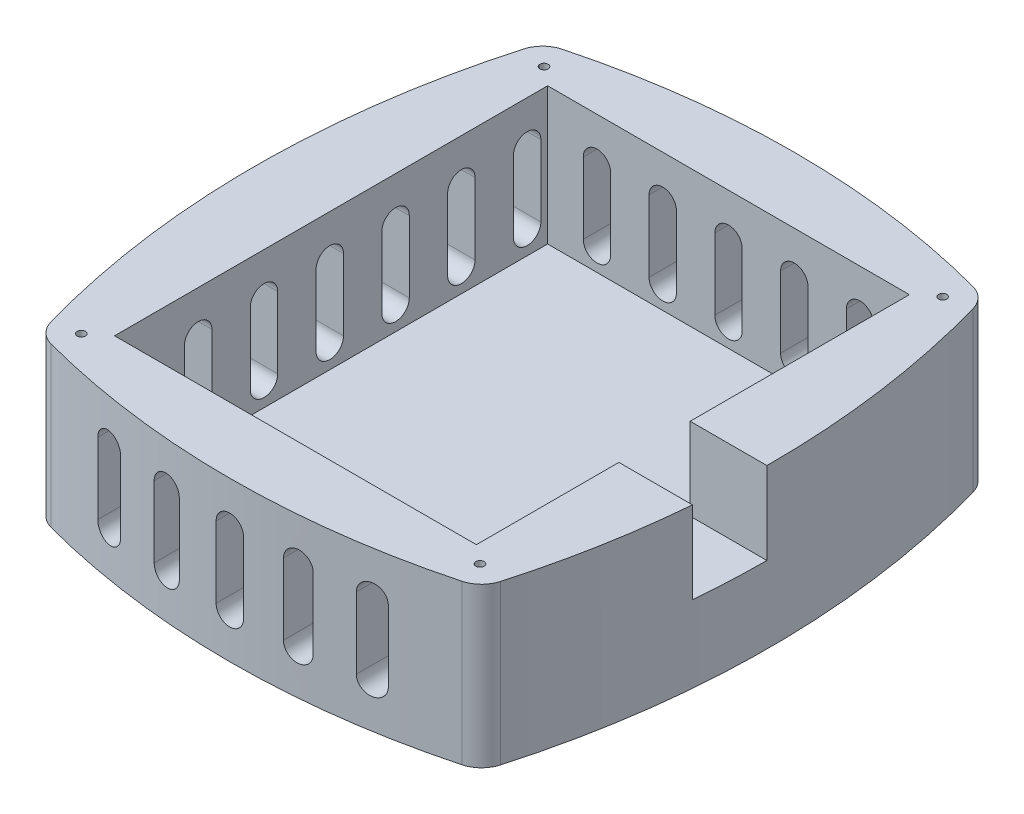
SolidWorks part; units mm, degrees
ref_plane "Front Plane" through (0, 0, 0) normal (0, 0, 1) x (1, 0, 0)
ref_plane "Top Plane" through (0, 0, 0) normal (0, 1, 0) x (1, 0, 0)
ref_plane "Right Plane" through (0, 0, 0) normal (1, 0, 0) x (0, 0, -1)
sketch "Sketch1" plane through (0, 0, 0) normal (0, 1, 0) x (1, 0, 0)
  line L0 (39.2475, 50.0745) -> (39.2475, -28.9255)
  line L1 (39.2475, -28.9255) -> (-26.7525, -28.9255)
  line L2 (-26.7525, -28.9255) -> (-26.7525, 50.0745)
  line L3 (-26.7525, 50.0745) -> (39.2475, 50.0745)
  dimension "D1" = 79
  dimension "D2" = 66
extrude "Boss-Extrude1" add sketch "Sketch1" along normal blind 4
sketch "Sketch2" plane through (0, 0, 0) normal (0, -1, 0) x (1, 0, 0)
  line L0 (-30.7525, 32.9255) -> (-30.7525, -54.0745)
  line L1 (-30.7525, -54.0745) -> (43.2475, -54.0745)
  line L2 (43.2475, -54.0745) -> (43.2475, 32.9255)
  line L3 (43.2475, 32.9255) -> (-30.7525, 32.9255)
  line L4 (-26.7525, -50.0745) -> (39.2475, -50.0745)
  line L5 (39.2475, -50.0745) -> (39.2475, 28.9255)
  line L6 (39.2475, 28.9255) -> (-26.7525, 28.9255)
  line L7 (-26.7525, 28.9255) -> (-26.7525, -50.0745)
  line L8 (-26.7525, -50.0745) -> (39.2475, -50.0745)
  line L9 (39.2475, -50.0745) -> (39.2475, 28.9255)
  line L10 (39.2475, 28.9255) -> (-26.7525, 28.9255)
  line L11 (-26.7525, 28.9255) -> (-26.7525, -50.0745)
  dimension "D1" = 0
  dimension "D2" = 4
extrude "Boss-Extrude2" add sketch "Sketch2" against normal blind 29
sketch "Sketch4" plane through (0, 0, 0) normal (0, -1, 0) x (1, 0, 0)
  line L0 (-30.7525, 32.9255) -> (-30.7525, -54.0745) construction
  line L1 (-30.7525, -10.5745) -> (43.2475, -10.5745) construction
  line L2 (43.2475, -54.0745) -> (43.2475, 32.9255) construction
  line L3 (6.2475, 32.9255) -> (6.2475, -10.5745) construction
  line L4 (43.2475, 32.9255) -> (-30.7525, 32.9255) construction
  line L5 (43.2475, 32.9255) -> (-30.7525, 32.9255) construction
  line L9 (-30.7525, -54.0745) -> (43.2475, -54.0745) construction
  line L10 (-30.7525, 32.9255) -> (-30.7525, -54.0745) construction
  line L11 (43.2475, 32.9255) -> (-30.7525, 32.9255)
  line L12 (43.2475, -54.0745) -> (43.2475, 32.9255)
  line L15 (-30.7525, -54.0745) -> (43.2475, -54.0745)
  line L16 (-30.7525, 32.9255) -> (-30.7525, -54.0745)
  arc A0 (-40.7525, -10.5745) -> (-34.7525, 32.5476) centre (117.2068, -10.5745) cw
  arc A1 (-40.7525, -10.5745) -> (-34.7525, -53.6965) centre (117.2068, -10.5745) ccw
  arc A2 (-34.7525, 32.5476) -> (-31.2309, 36.0137) centre (-29.9424, 31.1826) cw
  arc A3 (-31.2309, 36.0137) -> (6.2475, 40.9255) centre (6.2475, -104.5161) cw
  arc A4 (47.2475, 32.5476) -> (43.7258, 36.0137) centre (42.4374, 31.1826) ccw
  arc A5 (43.7258, 36.0137) -> (6.2475, 40.9255) centre (6.2475, -104.5161) ccw
  arc A6 (53.2475, -10.5745) -> (47.2475, -53.6965) centre (-104.7118, -10.5745) cw
  arc A7 (53.2475, -10.5745) -> (47.2475, 32.5476) centre (-104.7118, -10.5745) ccw
  arc A8 (-34.7525, -53.6965) -> (-31.2309, -57.1627) centre (-29.9424, -52.3316) ccw
  arc A9 (-31.2309, -57.1627) -> (6.2475, -62.0745) centre (6.2475, 83.3671) ccw
  arc A10 (43.7258, -57.1627) -> (6.2475, -62.0745) centre (6.2475, 83.3671) cw
  arc A11 (47.2475, -53.6965) -> (43.7258, -57.1627) centre (42.4374, -52.3316) cw
  dimension "D4" = 8
  dimension "D5" = 5
  dimension "D1" = 10
  dimension "D2" = 86.2441
  dimension "D3" = 4
extrude "Boss-Extrude4" add sketch "Sketch4" against normal up to surface (29 mm away) up to face at (6.2475, 29, -10.5745)
sketch "Sketch3" plane through (0, 29, 0) normal (0, 1, 0) x (1, 0, 0)
  line L0 (39.2475, -28.9255) -> (39.2475, 50.0745) construction
  line L1 (39.2475, 10.0745) -> (55.4463, 10.0745)
  line L2 (39.2475, 10.0745) -> (39.2475, -2.9255)
  line L3 (39.2475, -2.9255) -> (55.4463, -2.9255)
  line L6 (39.2475, 50.0745) -> (-26.7525, 50.0745) construction
  line L7 (-26.7525, 50.0745) -> (39.2475, 50.0745) construction
  line L8 (55.4463, -2.9255) -> (55.4463, 10.0745)
  dimension "D1" = 40
  dimension "D2" = 53
extrude "Cut-Extrude1" cut sketch "Sketch3" against normal blind 15
sketch "Sketch5" plane through (-26.7525, 0, 0) normal (1, 0, 0) x (0, 0, -1)
  line L0 (10.3372, 21.1129) -> (10.3372, 8.1129) construction
  line L1 (12.8372, 21.1129) -> (12.8372, 8.1129)
  line L2 (7.8372, 21.1129) -> (7.8372, 8.1129)
  line L3 (22.3372, 21.1129) -> (22.3372, 8.1129) construction
  line L4 (24.8372, 21.1129) -> (24.8372, 8.1129)
  line L5 (19.8372, 21.1129) -> (19.8372, 8.1129)
  line L6 (34.3372, 21.1129) -> (34.3372, 8.1129) construction
  line L7 (36.8372, 21.1129) -> (36.8372, 8.1129)
  line L8 (31.8372, 21.1129) -> (31.8372, 8.1129)
  line L9 (46.3372, 21.1129) -> (46.3372, 8.1129) construction
  line L10 (48.8372, 21.1129) -> (48.8372, 8.1129)
  line L11 (43.8372, 21.1129) -> (43.8372, 8.1129)
  line L12 (10.3372, 21.1129) -> (10.3372, 8.1129) construction
  line L13 (12.8372, 21.1129) -> (12.8372, 8.1129)
  line L14 (7.8372, 21.1129) -> (7.8372, 8.1129)
  line L15 (22.3372, 21.1129) -> (22.3372, 8.1129) construction
  line L16 (24.8372, 21.1129) -> (24.8372, 8.1129)
  line L17 (19.8372, 21.1129) -> (19.8372, 8.1129)
  line L18 (34.3372, 21.1129) -> (34.3372, 8.1129) construction
  line L19 (36.8372, 21.1129) -> (36.8372, 8.1129)
  line L20 (31.8372, 21.1129) -> (31.8372, 8.1129)
  line L21 (-1.6628, 21.1129) -> (-1.6628, 8.1129) construction
  line L22 (0.8372, 21.1129) -> (0.8372, 8.1129)
  line L23 (-4.1628, 21.1129) -> (-4.1628, 8.1129)
  line L24 (10.3372, 21.1129) -> (10.3372, 8.1129) construction
  line L25 (12.8372, 21.1129) -> (12.8372, 8.1129)
  line L26 (7.8372, 21.1129) -> (7.8372, 8.1129)
  line L27 (22.3372, 21.1129) -> (22.3372, 8.1129) construction
  line L28 (24.8372, 21.1129) -> (24.8372, 8.1129)
  line L29 (19.8372, 21.1129) -> (19.8372, 8.1129)
  line L30 (-13.6628, 21.1129) -> (-13.6628, 8.1129) construction
  line L31 (-11.1628, 21.1129) -> (-11.1628, 8.1129)
  line L32 (-16.1628, 21.1129) -> (-16.1628, 8.1129)
  line L33 (-1.6628, 21.1129) -> (-1.6628, 8.1129) construction
  line L34 (0.8372, 21.1129) -> (0.8372, 8.1129)
  line L35 (-4.1628, 21.1129) -> (-4.1628, 8.1129)
  line L36 (10.3372, 21.1129) -> (10.3372, 8.1129) construction
  line L37 (12.8372, 21.1129) -> (12.8372, 8.1129)
  line L38 (7.8372, 21.1129) -> (7.8372, 8.1129)
  line L39 (-1.6628, 21.1129) -> (-1.6628, 8.1129) construction
  line L40 (0.8372, 21.1129) -> (0.8372, 8.1129)
  line L41 (-4.1628, 21.1129) -> (-4.1628, 8.1129)
  line L42 (-13.6628, 21.1129) -> (-13.6628, 8.1129) construction
  line L43 (-11.1628, 21.1129) -> (-11.1628, 8.1129)
  line L44 (-16.1628, 21.1129) -> (-16.1628, 8.1129)
  line L45 (-25.6628, 21.1129) -> (-25.6628, 8.1129) construction
  line L46 (-23.1628, 21.1129) -> (-23.1628, 8.1129)
  line L47 (-28.1628, 21.1129) -> (-28.1628, 8.1129)
  arc A0 (12.8372, 21.1129) -> (7.8372, 21.1129) centre (10.3372, 21.1129) ccw
  arc A1 (7.8372, 8.1129) -> (12.8372, 8.1129) centre (10.3372, 8.1129) ccw
  arc A2 (24.8372, 21.1129) -> (19.8372, 21.1129) centre (22.3372, 21.1129) ccw
  arc A3 (19.8372, 8.1129) -> (24.8372, 8.1129) centre (22.3372, 8.1129) ccw
  arc A4 (36.8372, 21.1129) -> (31.8372, 21.1129) centre (34.3372, 21.1129) ccw
  arc A5 (31.8372, 8.1129) -> (36.8372, 8.1129) centre (34.3372, 8.1129) ccw
  arc A6 (48.8372, 21.1129) -> (43.8372, 21.1129) centre (46.3372, 21.1129) ccw
  arc A7 (43.8372, 8.1129) -> (48.8372, 8.1129) centre (46.3372, 8.1129) ccw
  arc A8 (12.8372, 21.1129) -> (7.8372, 21.1129) centre (10.3372, 21.1129) ccw
  arc A9 (7.8372, 8.1129) -> (12.8372, 8.1129) centre (10.3372, 8.1129) ccw
  arc A10 (24.8372, 21.1129) -> (19.8372, 21.1129) centre (22.3372, 21.1129) ccw
  arc A11 (19.8372, 8.1129) -> (24.8372, 8.1129) centre (22.3372, 8.1129) ccw
  arc A12 (36.8372, 21.1129) -> (31.8372, 21.1129) centre (34.3372, 21.1129) ccw
  arc A13 (31.8372, 8.1129) -> (36.8372, 8.1129) centre (34.3372, 8.1129) ccw
  arc A14 (0.8372, 21.1129) -> (-4.1628, 21.1129) centre (-1.6628, 21.1129) ccw
  arc A15 (-4.1628, 8.1129) -> (0.8372, 8.1129) centre (-1.6628, 8.1129) ccw
  arc A16 (12.8372, 21.1129) -> (7.8372, 21.1129) centre (10.3372, 21.1129) ccw
  arc A17 (7.8372, 8.1129) -> (12.8372, 8.1129) centre (10.3372, 8.1129) ccw
  arc A18 (24.8372, 21.1129) -> (19.8372, 21.1129) centre (22.3372, 21.1129) ccw
  arc A19 (19.8372, 8.1129) -> (24.8372, 8.1129) centre (22.3372, 8.1129) ccw
  arc A20 (-11.1628, 21.1129) -> (-16.1628, 21.1129) centre (-13.6628, 21.1129) ccw
  arc A21 (-16.1628, 8.1129) -> (-11.1628, 8.1129) centre (-13.6628, 8.1129) ccw
  arc A22 (0.8372, 21.1129) -> (-4.1628, 21.1129) centre (-1.6628, 21.1129) ccw
  arc A23 (-4.1628, 8.1129) -> (0.8372, 8.1129) centre (-1.6628, 8.1129) ccw
  arc A24 (12.8372, 21.1129) -> (7.8372, 21.1129) centre (10.3372, 21.1129) ccw
  arc A25 (7.8372, 8.1129) -> (12.8372, 8.1129) centre (10.3372, 8.1129) ccw
  arc A26 (0.8372, 21.1129) -> (-4.1628, 21.1129) centre (-1.6628, 21.1129) ccw
  arc A27 (-4.1628, 8.1129) -> (0.8372, 8.1129) centre (-1.6628, 8.1129) ccw
  arc A28 (-11.1628, 21.1129) -> (-16.1628, 21.1129) centre (-13.6628, 21.1129) ccw
  arc A29 (-16.1628, 8.1129) -> (-11.1628, 8.1129) centre (-13.6628, 8.1129) ccw
  arc A30 (-23.1628, 21.1129) -> (-28.1628, 21.1129) centre (-25.6628, 21.1129) ccw
  arc A31 (-28.1628, 8.1129) -> (-23.1628, 8.1129) centre (-25.6628, 8.1129) ccw
  point P2 (10.3372, 14.6129)
  point P12 (22.3372, 14.6129)
  point P19 (34.3372, 14.6129)
  point P26 (46.3372, 14.6129)
  point P33 (10.3372, 14.6129)
  point P40 (22.3372, 14.6129)
  point P47 (34.3372, 14.6129)
  point P54 (-1.6628, 14.6129)
  point P61 (10.3372, 14.6129)
  point P68 (22.3372, 14.6129)
  point P75 (-13.6628, 14.6129)
  point P82 (-1.6628, 14.6129)
  point P89 (10.3372, 14.6129)
  point P96 (-1.6628, 14.6129)
  point P103 (-13.6628, 14.6129)
  point P110 (-25.6628, 14.6129)
  dimension "D2" = 13
  dimension "D1" = 5
  dimension "D3" = 4
  dimension "D4" = 4
extrude "Cut-Extrude2" cut sketch "Sketch5" against normal blind 93 contours L32 A21 L31 A20 | L47 A31 L46 A30 | L23 A15 L22 A14 | L2 A1 L1 A0 | L5 A3 L4 A2 | L8 A5 L7 A4 | L11 A7 L10 A6
sketch "Sketch6" plane through (0, 0, 28.9255) normal (0, 0, -1) x (-1, 0, 0)
  line L0 (-6.2475, 21) -> (-6.2475, 8) construction
  line L1 (-3.7475, 21) -> (-3.7475, 8)
  line L2 (-8.7475, 21) -> (-8.7475, 8)
  line L3 (-53.2475, 14.5) -> (34.7525, 14.5) construction
  line L4 (-53.2475, 29) -> (-53.2475, 0) construction
  line L5 (34.7525, 29) -> (34.7525, 0) construction
  line L6 (-43.7258, 0) -> (31.2309, 0) construction
  arc A0 (-3.7475, 21) -> (-8.7475, 21) centre (-6.2475, 21) ccw
  arc A1 (-8.7475, 8) -> (-3.7475, 8) centre (-6.2475, 8) ccw
  point P2 (-6.2475, 14.5)
  point P15 (-6.2475, 0)
extrude "Cut-Extrude3" cut sketch "Sketch6" against normal blind 93
pattern_linear "LPattern1" count 3 spacing 12 along (1, 0, 0) count 3 spacing 12 along (-1, 0, 0) of "Cut-Extrude3"
ref_plane "Plane1" through (0, 0, -10.5745) normal (0, 0, 1) x (1, 0, 0)
mirror "Mirror1" about plane through (0, 0, -10.5745) normal (0, 0, 1) of "Cut-Extrude3", "LPattern1"
hole_wizard "#17 (0.173) Diameter Hole1" positions "Sketch9" profile "Sketch8" hole size "#17" standard "ANSI Inch"
sketch "Sketch9" plane through (0, 29, 0) normal (0, 1, 0) x (1, 0, 0)
  line L0 (6.2475, 62.0745) -> (6.2475, -40.9255) construction
  line L2 (-40.7525, 10.5745) -> (53.2475, 10.5745) construction
  arc A0 (43.7258, 57.1627) -> (-31.2309, 57.1627) centre (6.2475, -83.3671) ccw construction
  arc A1 (-31.2309, -36.0137) -> (43.7258, -36.0137) centre (6.2475, 104.5161) ccw construction
  arc A2 (-34.7525, 53.6965) -> (-34.7525, -32.5476) centre (117.2068, 10.5745) ccw construction
  arc A3 (53.2467, 10.0745) -> (47.2475, 53.6965) centre (-104.7118, 10.5745) ccw construction
  point P0 (-30.1172, 52.7797)
  point P24 (-30.1172, -31.6307)
  point P26 (42.6121, -31.6307)
  point P27 (42.6121, 52.7797)
sketch "Sketch8" plane through (-30.1172, 29, -52.7797) normal (1, 0, 0) x (0, 0, 1)
  line L0 (0, 0) -> (0, 10.4506)
  line L1 (0, 10.4506) -> (0.75, 10)
  line L2 (0.75, 10) -> (0.75, 0)
  line L5 (0.75, 0) -> (0, 0)
  line L10 (0, 10.4506) -> (-0.75, 10) construction
  line L11 (0, -6.35) -> (0, 107.95) construction
  dimension "Hole Dia." = 1.5
  dimension "Hole Depth" = 10
  dimension "Drill Angle" = 118
